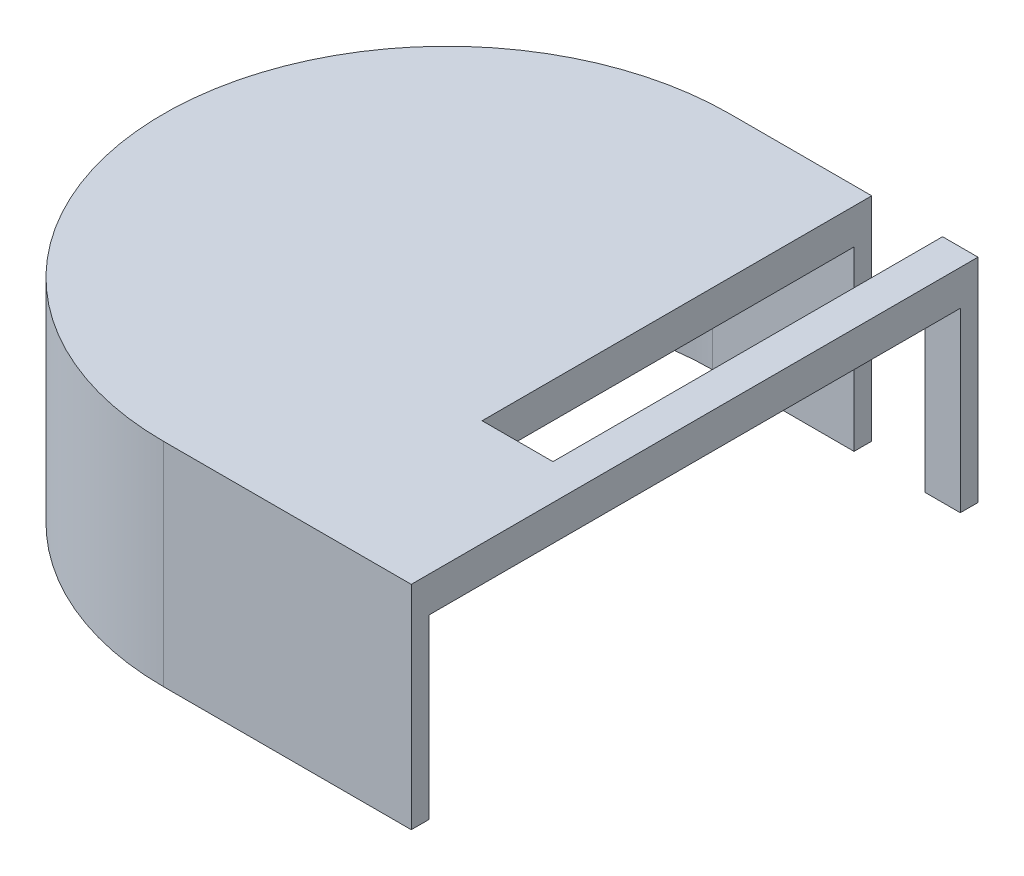
SolidWorks part; units mm, degrees
ref_plane "Front Plane" through (0, 0, 0) normal (0, 0, 1) x (1, 0, 0)
ref_plane "Top Plane" through (0, 0, 0) normal (0, 1, 0) x (1, 0, 0)
ref_plane "Right Plane" through (0, 0, 0) normal (1, 0, 0) x (0, 0, -1)
sketch "Sketch1" plane through (0, 0, 0) normal (0, 1, 0) x (1, 0, 0)
  line L11 (0, 8) -> (7, 8)
  line L13 (0, -8) -> (7, -8)
  line L19 (7, 8) -> (7, -8)
  arc A4 (0, 8) -> (0, -8) centre (0, 0) ccw
  point P4 (0, 0)
  point P5 (0, 0)
  point P6 (0, 0)
  point P7 (7, -7.6672)
  point P8 (0, 0)
  point P9 (0, 0)
  point P11 (0, 0)
  point P12 (0, 0)
  point P13 (6.9371, 7)
  point P14 (0, 0)
  point P15 (0, 0)
  point P16 (0, 0)
  point P17 (0, 0)
  dimension "D1" = 7
  dimension "D3" = 8
  dimension "D6" = 16
extrude "Boss-Extrude1" add sketch "Sketch1" along normal blind 1 contours A4 L13 L19 L11
sketch "Sketch5" plane through (0, 0, 0) normal (0, -1, 0) x (1, 0, 0)
  line L11 (0, 8) -> (7, 8)
  line L13 (0, -8) -> (7, -8)
  line L15 (0, 7.5) -> (7, 7.5)
  line L16 (0, -7.5) -> (7, -7.5)
  line L17 (7, 8) -> (7, 7.5)
  line L18 (7, -7.5) -> (7, -8)
  arc A4 (0, 8) -> (0, -8) centre (0, 0) ccw
  arc A5 (0, 7.5) -> (0, -7.5) centre (0, 0) ccw
  point P4 (0, 0)
  point P6 (0, 0)
  point P11 (0, 0)
  point P12 (0, 0)
  dimension "D1" = 7
  dimension "D3" = 8
  dimension "D2" = 7.5
  dimension "D4" = 0.5
  dimension "D5" = 7
  dimension "D6" = 16
extrude "Boss-Extrude3" add sketch "Sketch5" along normal blind 5
sketch "Sketch6" plane through (0, 1, 0) normal (0, 1, 0) x (1, 0, 0)
  line L0 (0, 8) -> (7, 8) construction
  line L1 (6, -3) -> (4, -3)
  line L2 (6, -3) -> (6, 8)
  line L3 (6, 8) -> (4, 8)
  line L4 (4, -3) -> (4, 8)
  line L6 (7, 8) -> (7, -8) construction
  dimension "D1" = 1
  dimension "D2" = 2
  dimension "D3" = 11
extrude "Cut-Extrude1" cut sketch "Sketch6" against normal blind 7
sketch "Sketch7" plane through (0, 0, 7.5) normal (0, 0, -1) x (-1, 0, 0)
  line L0 (0, 0) -> (-7, 0) construction
  circle A0 centre (-4.0675, -3.5) radius 1.5
  point P2 (1.0278, -16.4693)
  point P3 (0.5667, -16.5083)
  point P4 (0.5245, -16.5335)
  point P5 (0.9261, -18.0053)
  point P6 (0.9261, -18.0053)
  point P7 (-3.4385, -3.7203)
  point P10 (-3.9748, -3.5)
  point P11 (-4.0128, -3.5)
  point P12 (0, 0)
  point P13 (-2.6461, -3.5)
  point P14 (-1.7999, -3.5)
  point P15 (-4.0675, -3.5)
  dimension "D1" = 3.5
  dimension "D2" = 3
extrude "Boss-Extrude4" add sketch "Sketch7" along normal blind 1
